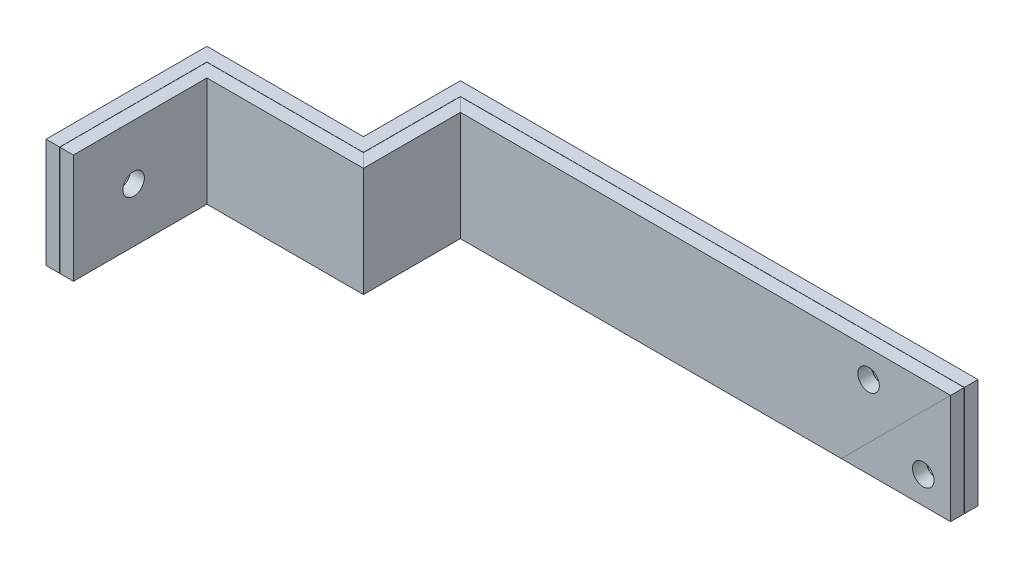
SolidWorks part; units mm, degrees
ref_plane "Alzado" through (0, 0, 0) normal (0, 0, 1) x (1, 0, 0)
ref_plane "Planta" through (0, 0, 0) normal (0, 1, 0) x (1, 0, 0)
ref_plane "Vista lateral" through (0, 0, 0) normal (1, 0, 0) x (0, 0, -1)
sketch "Croquis2" plane through (0, 0, 0) normal (1, 0, 0) x (0, 0, -1)
  line L1 (-3.155, 25.4) -> (3.155, 25.4)
  line L2 (-3.155, 25.4) -> (-3.155, -25.4)
  line L3 (-3.155, -25.4) -> (3.155, -25.4)
  line L4 (3.155, 25.4) -> (3.155, -25.4)
  line L5 (-3.155, 25.4) -> (3.155, -25.4) construction
  line L6 (-3.155, -25.4) -> (3.155, 25.4) construction
  point P0 (0, 0)
  dimension "D1" = 50.8
  dimension "D2" = 6.31
sketch3d "Croquis3D1"
  line L0 (0, 0, 0) -> (75.84, 0, 0)
  line L1 (75.84, 0, 0) -> (75.84, 0, -45)
  line L2 (75.84, 0, -45) -> (281.23, 0, -45)
  line L3 (281.23, 0, -45) -> (281.23, -388, -45)
  dimension "D1" = 75.84
  dimension "D2" = 45
  dimension "D3" = 205.39
  dimension "D4" = 388
sweep "Barrer1" add profiles "Croquis2" path "Croquis3D1"
sketch "Croquis3" plane through (0, 0, 3.155) normal (0, 0, 1) x (1, 0, 0)
  line L0 (0, 0) -> (75.84, 0) construction
  line L1 (6.31, 25.4) -> (0, 25.4)
  line L2 (6.31, 25.4) -> (6.31, -25.4)
  line L3 (6.31, -25.4) -> (0, -25.4)
  line L4 (0, 25.4) -> (0, -25.4)
  line L5 (6.31, 25.4) -> (0, -25.4) construction
  line L6 (6.31, -25.4) -> (0, 25.4) construction
  point P0 (3.155, 0)
  dimension "D1" = 6.31
extrude "Saliente-Extruir1" add sketch "Croquis3" along normal blind 62
sketch "Croquis4" plane through (0, 0, -41.845) normal (0, 0, 1) x (1, 0, 0)
  line L0 (255.83, -388) -> (255.83, -337.2)
  line L1 (255.83, -25.4) -> (255.83, -388) construction
  line L2 (255.83, -337.2) -> (262.14, -337.2)
  line L3 (262.14, -337.2) -> (262.14, -388)
  line L4 (306.63, -388) -> (255.83, -388) construction
  line L5 (262.14, -388) -> (255.83, -388)
  dimension "D1" = 6.31
  dimension "D2" = 50.8
extrude "Saliente-Extruir2" add sketch "Croquis4" along normal blind 40
sketch "Croquis5" plane through (262.14, 0, 0) normal (1, 0, 0) x (0, 0, -1)
  line L0 (16.155, -346.6) -> (16.155, -378.6) construction
  circle A0 centre (16.155, -346.6) radius 6.35
  circle A1 centre (16.155, -378.6) radius 6.35
extrude "Cortar-Extruir1" cut sketch "Croquis5" against normal blind 10
sketch "Croquis6" plane through (0, 0, 0) normal (-1, 0, 0) x (0, 0, 1)
  line L0 (65.155, 25.4) -> (65.155, 19.09)
  line L1 (65.155, 25.4) -> (65.155, -25.4) construction
  line L2 (65.155, 19.09) -> (14.355, 19.09)
  line L3 (14.355, 19.09) -> (14.355, 25.4)
  line L4 (-3.155, 25.4) -> (65.155, 25.4) construction
  line L5 (14.355, 25.4) -> (65.155, 25.4)
  dimension "D1" = 50.8
  dimension "D2" = 6.31
extrude "Saliente-Extruir3" add sketch "Croquis6" along normal blind 50.8
sketch "Croquis7" plane through (0, 0, -48.155) normal (0, 0, -1) x (-1, 0, 0)
  line L0 (-255.83, -25.4) -> (-306.63, -25.4)
  line L1 (-306.63, 25.4) -> (-306.63, -388) construction
  line L2 (-306.63, -25.4) -> (-306.63, -388)
  line L3 (-306.63, -388) -> (-255.83, -388)
  line L4 (-255.83, -388) -> (-255.83, -25.4)
extrude "Cortar-Extruir2" cut sketch "Croquis7" against normal blind 67
sketch "Croquis8" plane through (0, 19.09, 0) normal (0, -1, 0) x (1, 0, 0)
  line L0 (0, 14.355) -> (0, 65.155)
  line L1 (0, 65.155) -> (-50.8, 65.155)
  line L2 (-50.8, 65.155) -> (-50.8, 14.355)
  line L3 (-50.8, 14.355) -> (0, 14.355)
extrude "Cortar-Extruir3" cut sketch "Croquis8" against normal blind 67
sketch "Croquis9" plane through (0, -25.4, 0) normal (0, -1, 0) x (1, 0, 0)
  line L0 (-0.1, 65.155) -> (-1.9255, 65.155)
  line L1 (-1.9255, 65.155) -> (-6.41, 65.155)
  line L2 (-6.41, 65.155) -> (-6.41, -9.565)
  line L3 (-6.41, -9.565) -> (66.275, -9.565)
  line L4 (66.275, -9.565) -> (66.275, -54.565)
  line L5 (66.275, -54.565) -> (306.63, -54.565)
  line L6 (306.63, -48.155) -> (306.63, -63.9079) construction
  line L7 (-0.1, -3.255) -> (-0.1, 65.155)
  line L8 (306.63, -48.255) -> (306.63, -54.565)
  line L9 (0, 65.155) -> (-1.9255, 65.155) construction
  line L10 (-0.1, -3.255) -> (72.585, -3.255)
  line L11 (72.585, -3.255) -> (72.585, -48.255)
  line L12 (72.585, -48.255) -> (306.63, -48.255)
  line L13 (255.83, -48.155) -> (306.63, -48.155) construction
  line L14 (72.685, -3.155) -> (72.685, -48.155) construction
  line L15 (0, -3.155) -> (72.685, -3.155) construction
  line L17 (0, 58.845) -> (-0.1, 58.845) construction
  line L19 (-0.1, 58.845) -> (-0.1, -3.255) construction
  line L20 (-0.1, 58.845) -> (-0.1, 58.845) construction
  dimension "D2" = 0.1
  dimension "D3" = 0.1
  dimension "D4" = 0.1
  dimension "D1" = 6.31
extrude "Saliente-Extruir4" add sketch "Croquis9" against normal blind 50.8 separate body
sketch "Croquis10" plane through (6.31, 0, 0) normal (1, 0, 0) x (0, 0, -1)
  line L0 (-32.195, -0.1722) -> (-37.195, -0.1722) construction
  circle A0 centre (-37.195, -0.1722) radius 5
extrude "Cortar-Extruir4" cut sketch "Croquis10" against normal blind 24.525
sketch "Croquis11" plane through (0, 0, -41.845) normal (0, 0, 1) x (1, 0, 0)
  line L0 (306.63, 25.4) -> (306.63, -25.4) construction
  line L1 (306.63, -25.4) -> (255.83, -25.4) construction
  line L2 (306.63, -25.4) -> (255.83, -25.4) construction
  line L3 (255.83, -25.4) -> (255.83, 25.4) construction
  line L4 (78.995, 25.4) -> (306.63, 25.4) construction
  line L5 (255.83, 25.4) -> (306.63, 25.4) construction
  line L6 (255.83, 25.4) -> (306.63, -25.4) construction
  line L7 (306.63, -25.4) -> (281.23, 0) construction
  line L8 (281.23, 0) -> (293.93, -12.7) construction
  line L9 (293.93, -12.7) -> (293.93, -16.1525) construction
  line L10 (281.23, 0) -> (255.83, 25.4) construction
  line L11 (255.83, 25.4) -> (268.53, 12.7) construction
  circle A0 centre (293.93, -12.7) radius 5
  circle A1 centre (268.53, 12.7) radius 5
  dimension "D2" = 10
  dimension "D3" = 10
  dimension "D1" = 50.8
extrude "Cortar-Extruir5" cut sketch "Croquis11" against normal blind 35
